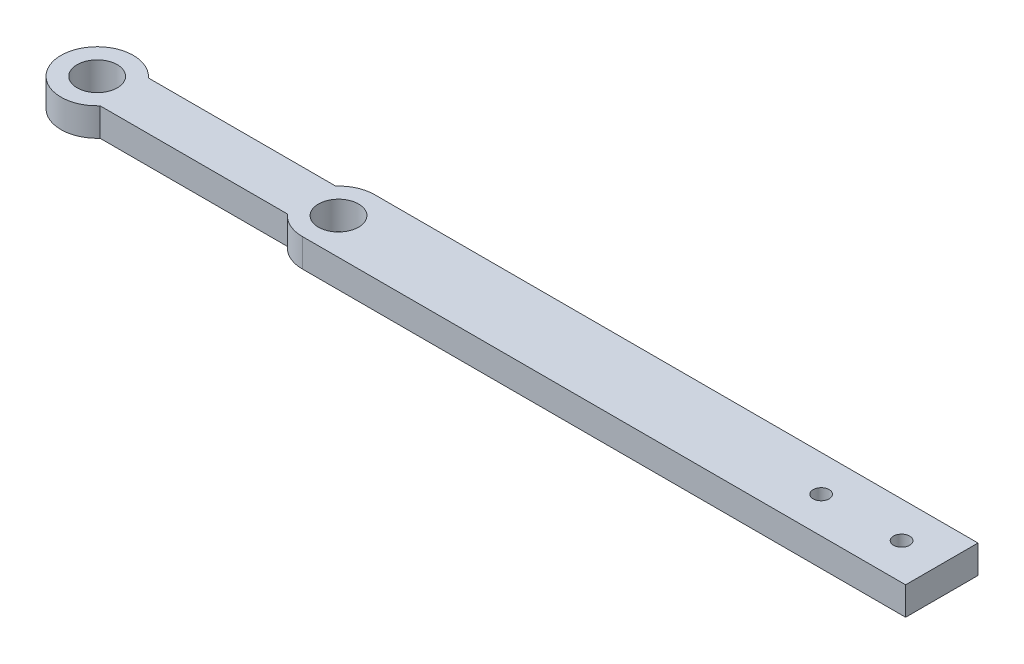
SolidWorks part; units mm, degrees
ref_plane "Front Plane" through (0, 0, 0) normal (0, 0, 1) x (1, 0, 0)
ref_plane "Top Plane" through (0, 0, 0) normal (0, 1, 0) x (1, 0, 0)
ref_plane "Right Plane" through (0, 0, 0) normal (1, 0, 0) x (0, 0, -1)
sketch "Sketch1" plane through (0, 0, 0) normal (0, 1, 0) x (1, 0, 0)
  line L5 (6.7082, 6) -> (53.2918, 6)
  line L6 (6.7082, -6) -> (53.2918, -6)
  line L7 (60, 9) -> (210, 9)
  line L8 (210, 9) -> (210, -9)
  line L9 (210, -9) -> (60, -9)
  arc A3 (6.7082, 6) -> (6.7082, -6) centre (0, 0) ccw
  arc A4 (53.2918, -6) -> (60, -9) centre (60, 0) ccw
  arc A5 (60, 9) -> (53.2918, 6) centre (60, 0) ccw
  point P2 (0, 0)
  point P13 (55.1248, 4.1631)
  point P14 (55.1248, -3.668)
  dimension "D1" = 18
  dimension "D2" = 18
  dimension "D3" = 60
  dimension "D4" = 6
  dimension "D5" = 150
extrude "Boss-Extrude1" add sketch "Sketch1" along normal blind 7
sketch "Sketch2" plane through (0, 7, 0) normal (0, 1, 0) x (1, 0, 0)
  circle A0 centre (0, 0) radius 5
  circle A1 centre (60, 0) radius 5
  dimension "D1" = 10
extrude "Cut-Extrude1" cut sketch "Sketch2" against normal through all
sketch "Sketch3" plane through (0, 7, 0) normal (0, 1, 0) x (1, 0, 0)
  line L0 (210, -9) -> (210, 9) construction
  circle A0 centre (200, 0) radius 2
  circle A1 centre (180, 0) radius 2
  point P6 (0, 0)
  point P7 (0, 0)
  dimension "D3" = 4
  dimension "D1" = 10
  dimension "D2" = 20
extrude "Cut-Extrude2" cut sketch "Sketch3" against normal through all
